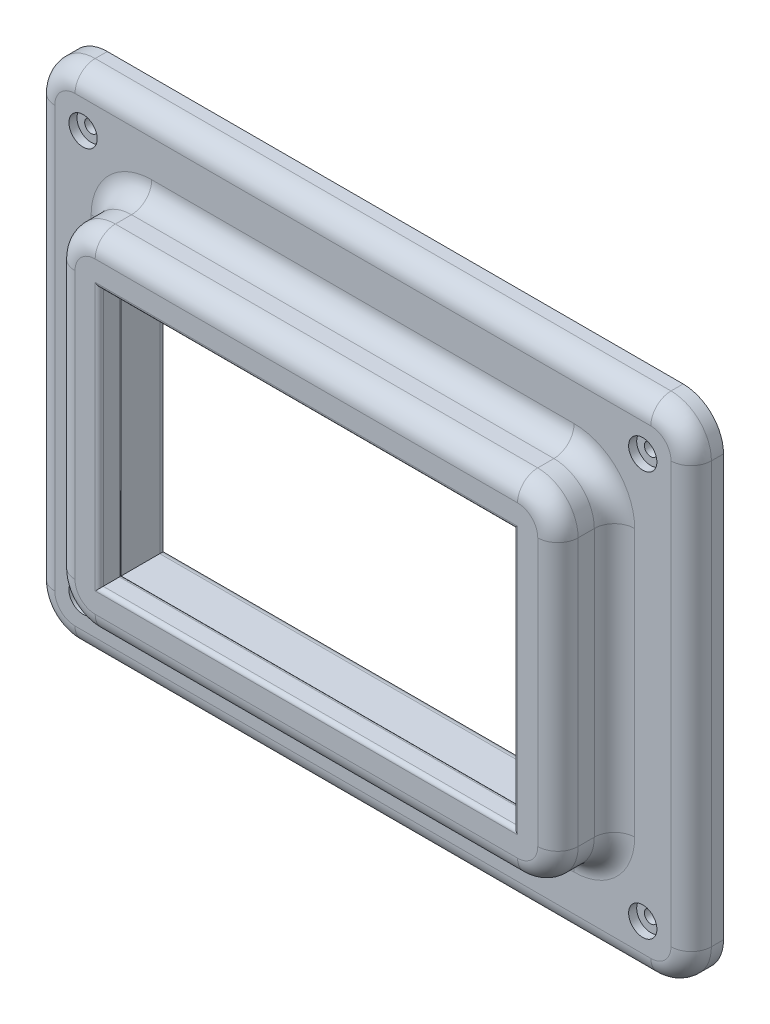
SolidWorks part; units mm, degrees
ref_plane "정면" through (0, 0, 0) normal (0, 0, 1) x (1, 0, 0)
ref_plane "윗면" through (0, 0, 0) normal (0, 1, 0) x (1, 0, 0)
ref_plane "우측면" through (0, 0, 0) normal (1, 0, 0) x (0, 0, -1)
sketch "스케치1" plane through (0, 0, 0) normal (0, 0, 1) x (1, 0, 0)
  line L0 (69.3, 50.1) -> (-69.3, 50.1) construction
  line L1 (-51.3, 32.1) -> (51.3, 32.1)
  line L2 (-51.3, 32.1) -> (-51.3, -32.1)
  line L3 (-51.3, -32.1) -> (51.3, -32.1)
  line L4 (51.3, 32.1) -> (51.3, -32.1)
  line L5 (-81.3, 62.1) -> (81.3, 62.1)
  line L6 (-81.3, 62.1) -> (-81.3, -62.1)
  line L7 (-81.3, -62.1) -> (81.3, -62.1)
  line L8 (81.3, 62.1) -> (81.3, -62.1)
  line L9 (-69.3, 50.1) -> (-69.3, -50.1) construction
  line L10 (-69.3, -50.1) -> (69.3, -50.1) construction
  line L11 (69.3, -50.1) -> (69.3, 50.1) construction
  circle A0 centre (-69.3, -50.1) radius 1.6
  circle A1 centre (69.3, -50.1) radius 1.6
  circle A2 centre (69.3, 50.1) radius 1.6
  circle A3 centre (-69.3, 50.1) radius 1.6
  point P8 (0, 32.1)
  point P10 (51.3, 0)
  point P19 (0, 50.1)
  point P20 (69.3, 0)
  point P21 (0, 62.1)
  point P22 (-81.3, 0)
  dimension "D7" = 3.2
  dimension "D1" = 102.6
  dimension "D2" = 64.2
  dimension "D3" = 30
  dimension "D4" = 30
  dimension "D8" = 12
  dimension "D9" = 12
extrude "보스-돌출1" add sketch "스케치1" along normal blind 22
sketch "스케치2" plane through (0, 0, 22) normal (0, 0, 1) x (1, 0, 0)
  circle A0 centre (-69.3, 50.1) radius 3.5
  circle A1 centre (69.3, 50.1) radius 3.5
  circle A2 centre (69.3, -50.1) radius 3.5
  circle A3 centre (-69.3, -50.1) radius 3.5
  dimension "D1" = 7
extrude "컷-돌출1" cut sketch "스케치2" against normal offset from surface (16 mm away) 6 up to face at (0, 0, 0)
sketch "스케치3" plane through (0, 0, 0) normal (0, 0, -1) x (-1, 0, 0)
  line L0 (51.3, -32.1) -> (-51.3, -32.1) construction
  line L1 (56.3, -37.1) -> (-56.3, -37.1)
  line L2 (56.3, -37.1) -> (56.3, 37.1)
  line L3 (56.3, 37.1) -> (-56.3, 37.1)
  line L4 (-56.3, -37.1) -> (-56.3, 37.1)
  line L5 (-51.3, -32.1) -> (-51.3, 32.1) construction
  point P4 (0, -37.1)
  point P6 (-56.3, 0)
  dimension "D1" = 5
  dimension "D2" = 5
extrude "컷-돌출2" cut sketch "스케치3" against normal offset from surface (16 mm away) 6 up to face at (72.8, 50.1, 22)
sketch "스케치4" plane through (0, 0, 22) normal (0, 0, 1) x (1, 0, 0)
  line L0 (51.3, 32.1) -> (-51.3, 32.1) construction
  line L1 (-81.3, 62.1) -> (81.3, 62.1)
  line L2 (-81.3, 62.1) -> (-81.3, -62.1)
  line L3 (-81.3, -62.1) -> (81.3, -62.1)
  line L4 (81.3, 62.1) -> (81.3, -62.1)
  line L5 (-62.3, 43.1) -> (62.3, 43.1)
  line L6 (-62.3, 43.1) -> (-62.3, -43.1)
  line L7 (-62.3, -43.1) -> (62.3, -43.1)
  line L8 (62.3, 43.1) -> (62.3, -43.1)
  line L9 (51.3, -32.1) -> (51.3, 32.1) construction
  point P10 (0, 43.1)
  point P12 (62.3, 0)
  dimension "D1" = 11
  dimension "D2" = 11
extrude "컷-돌출3" cut sketch "스케치4" against normal offset from surface (14 mm away) 8 up to face at (0, 0, 0)
fillet "필렛1" radius 10 8 edges at (81.3, 62.1, 4) (81.3, -62.1, 4) (-81.3, -62.1, 4) (-81.3, 62.1, 4) (62.3, -43.1, 15) (62.3, 43.1, 15) (-62.3, 43.1, 15) (-62.3, -43.1, 15)
fillet "필렛2" radius 5 16 edges at (-78.3711, 59.1711, 8) (0, 62.1, 8) (78.3711, 59.1711, 8) (81.3, 0, 8) (78.3711, -59.1711, 8) (0, -62.1, 8) (-78.3711, -59.1711, 8) (-81.3, 0, 8) (59.3711, -40.1711, 22) (0, -43.1, 22) (-59.3711, -40.1711, 22) (-62.3, 0, 22) (-59.3711, 40.1711, 22) (0, 43.1, 22) (59.3711, 40.1711, 22) (62.3, 0, 22)
fillet "필렛3" radius 1 4 edges at (51.3, 0, 22) (0, -32.1, 22) (-51.3, 0, 22) (0, 32.1, 22)
fillet "필렛4" radius 2 4 edges at (0, -37.1, 0) (-56.3, 0, 0) (56.3, 0, 0) (0, 37.1, 0)
fillet "필렛5" radius 1 4 edges at (-51.3, 0, 16) (0, -32.1, 16) (51.3, 0, 16) (0, 32.1, 16)
fillet "필렛6" radius 5 8 edges at (-59.3711, -40.1711, 8) (0, -43.1, 8) (59.3711, -40.1711, 8) (62.3, 0, 8) (59.3711, 40.1711, 8) (0, 43.1, 8) (-59.3711, 40.1711, 8) (-62.3, 0, 8)
